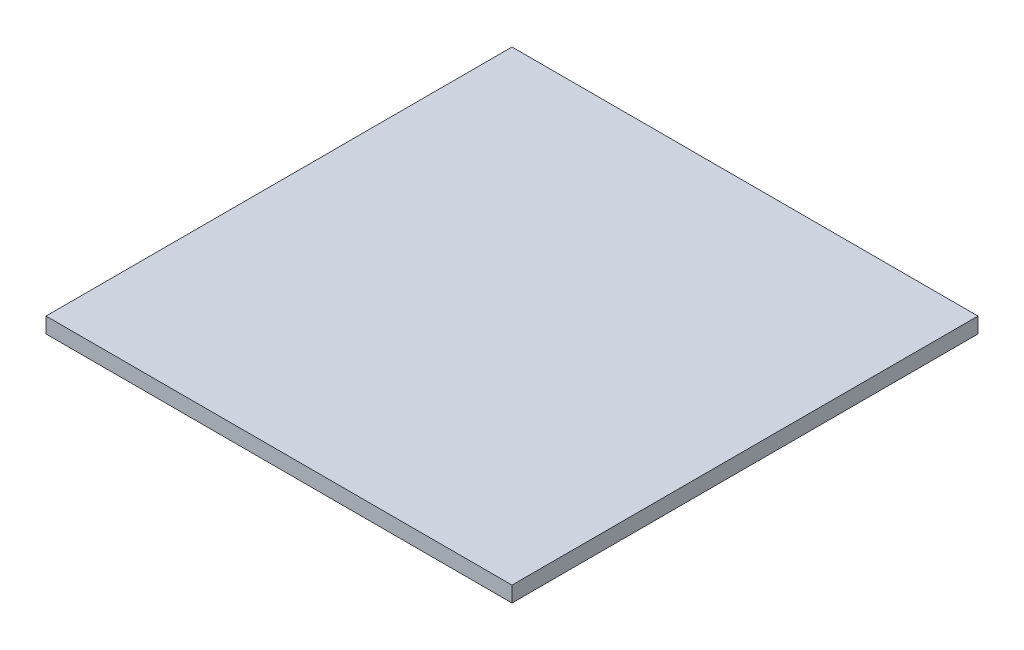
SolidWorks part; units mm, degrees
ref_plane "Front Plane" through (0, 0, 0) normal (0, 0, 1) x (1, 0, 0)
ref_plane "Top Plane" through (0, 0, 0) normal (0, 1, 0) x (1, 0, 0)
ref_plane "Right Plane" through (0, 0, 0) normal (1, 0, 0) x (0, 0, -1)
sketch "Sketch1" plane through (0, 0, 0) normal (0, 1, 0) x (1, 0, 0)
  line L1 (-30, 30) -> (30, 30)
  line L2 (-30, 30) -> (-30, -30)
  line L3 (-30, -30) -> (30, -30)
  line L4 (30, 30) -> (30, -30)
  line L5 (-30, 30) -> (30, -30) construction
  line L6 (-30, -30) -> (30, 30) construction
  point P0 (0, 0)
  dimension "D1" = 60
extrude "Boss-Extrude1" add sketch "Sketch1" along normal mid plane 2
